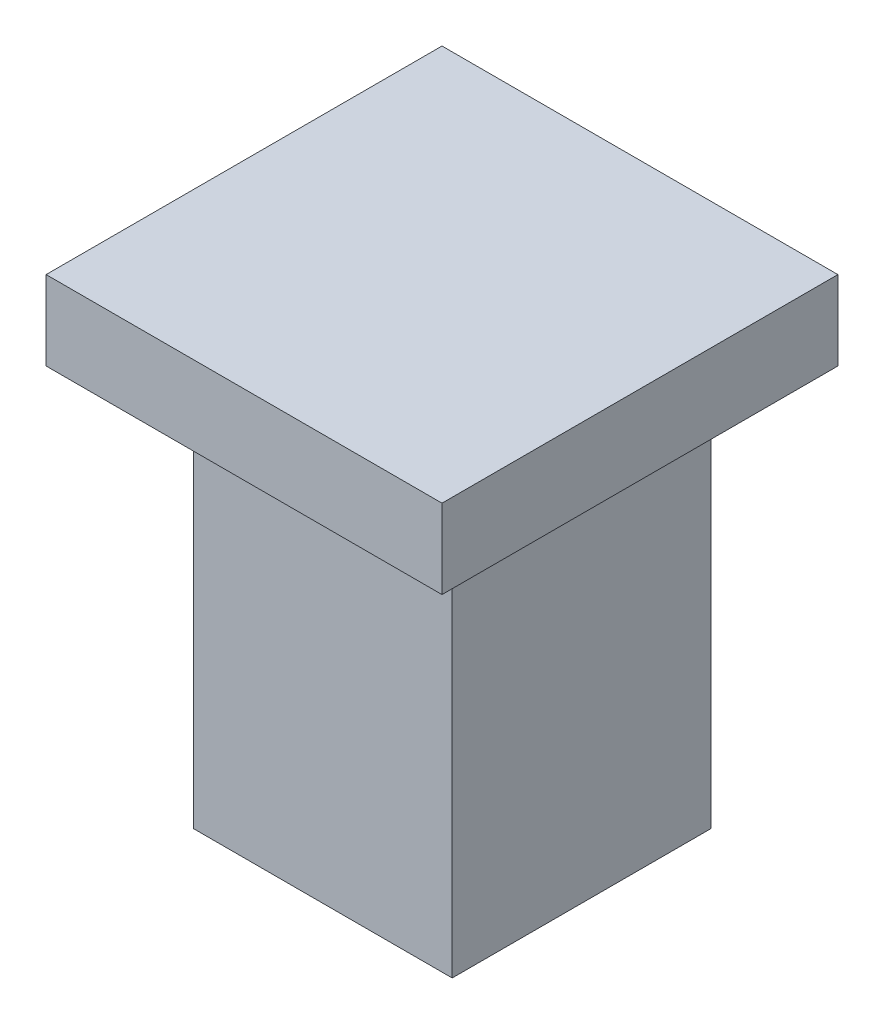
SolidWorks part; units mm, degrees
ref_plane "Front Plane" through (0, 0, 0) normal (0, 0, 1) x (1, 0, 0)
ref_plane "Top Plane" through (0, 0, 0) normal (0, 1, 0) x (1, 0, 0)
ref_plane "Right Plane" through (0, 0, 0) normal (1, 0, 0) x (0, 0, -1)
other "Bounding Box"
ref_plane "Default Plane" through (-7.8741, 18, -7.4876) normal (1, 0, 0) x (0, 0, -1)
sketch "Sketch1" plane through (0, 0, 0) normal (0, 1, 0) x (1, 0, 0)
  line L1 (-4.9, -4.9) -> (4.9, -4.9)
  line L2 (-4.9, -4.9) -> (-4.9, 4.9)
  line L3 (-4.9, 4.9) -> (4.9, 4.9)
  line L4 (4.9, -4.9) -> (4.9, 4.9)
  line L5 (-4.9, -4.9) -> (4.9, 4.9) construction
  line L6 (-4.9, 4.9) -> (4.9, -4.9) construction
  point P0 (0, 0)
  dimension "D1" = 9.8
  dimension "D2" = 9.8
extrude "Boss-Extrude1" add sketch "Sketch1" along normal blind 15
sketch "Sketch2" plane through (0, 15, 0) normal (0, 1, 0) x (1, 0, 0)
  line L1 (-7.8741, -7.5124) -> (7.1259, -7.5124)
  line L2 (-7.8741, -7.5124) -> (-7.8741, 7.4876)
  line L3 (-7.8741, 7.4876) -> (7.1259, 7.4876)
  line L4 (7.1259, -7.5124) -> (7.1259, 7.4876)
  line L5 (-7.8741, -7.5124) -> (7.1259, 7.4876) construction
  line L6 (-7.8741, 7.4876) -> (7.1259, -7.5124) construction
  point P0 (-0.3741, -0.0124)
  dimension "D1" = 15
  dimension "D2" = 15
extrude "Boss-Extrude2" add sketch "Sketch2" along normal blind 3
